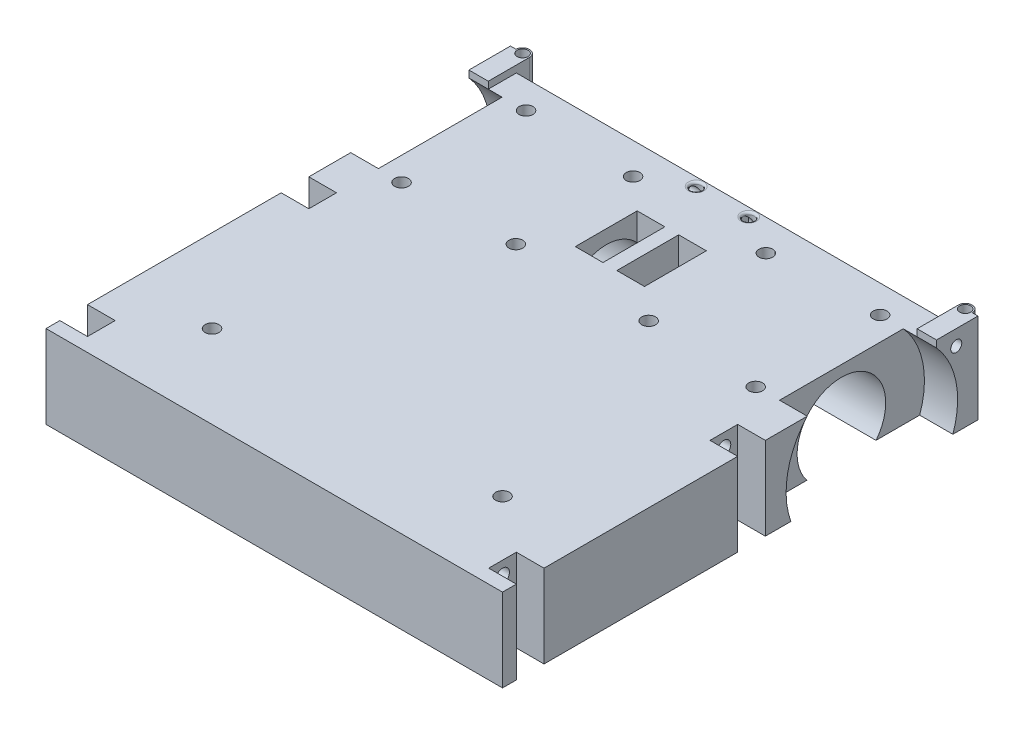
SolidWorks part; units mm, degrees
ref_plane "Plan de face" through (0, 0, 0) normal (0, 0, 1) x (1, 0, 0)
ref_plane "Plan de dessus" through (0, 0, 0) normal (0, 1, 0) x (1, 0, 0)
ref_plane "Plan de droite" through (0, 0, 0) normal (1, 0, 0) x (0, 0, -1)
sketch "Esquisse2" plane through (0, 0, 0) normal (0, 1, 0) x (1, 0, 0)
  line L1 (82.5, 82.5) -> (-82.5, 82.5)
  line L2 (82.5, 82.5) -> (82.5, -82.5)
  line L3 (82.5, -82.5) -> (-82.5, -82.5)
  line L4 (-82.5, 82.5) -> (-82.5, -82.5)
  line L5 (82.5, 82.5) -> (-82.5, -82.5) construction
  line L6 (82.5, -82.5) -> (-82.5, 82.5) construction
  point P0 (0, 0)
  dimension "D1" = 165
  dimension "D2" = 165
extrude "BASE" add sketch "Esquisse2" along normal blind 30
sketch "Esquisse3" plane through (82.5, 0, 0) normal (1, 0, 0) x (0, 0, -1)
  line L0 (82.5, 10) -> (31.0775, 10) construction
  line L1 (82.5, 30) -> (82.5, 0) construction
  line L2 (-82.5, 0) -> (82.5, 0) construction
  circle A0 centre (50, 10) radius 15
  point P4 (50, 10)
  dimension "D3" = 30
  dimension "D1" = 32.5
  dimension "D2" = 10
extrude "BLOC MOTEUR 1." cut sketch "Esquisse3" against normal blind 80
sketch "Esquisse4" plane through (0, 0, 0) normal (0, -1, 0) x (1, 0, 0)
  line L0 (2.5, -61.1803) -> (82.5, -61.1803) construction
  line L1 (2.5, -38.8197) -> (12.5, -38.8197)
  line L2 (2.5, -38.8197) -> (2.5, -61.1803)
  line L3 (2.5, -61.1803) -> (12.5, -61.1803)
  line L4 (12.5, -38.8197) -> (12.5, -61.1803)
  dimension "D1" = 10
extrude "ACCES MOTEUR" cut sketch "Esquisse4" against normal blind 37
ref_plane "PLAN SYM " through (0, 0, 0) normal (1, 0, 0) x (0, 0, -1)
sketch "Esquisse6" plane through (82.5, 0, 0) normal (1, 0, 0) x (0, 0, -1)
  line L0 (35, 10) -> (65, 10) construction
  arc A0 (38.8197, 20) -> (38.8197, 0) centre (50, 10) ccw construction
  arc A1 (61.1803, 0) -> (38.8197, 0) centre (50, 10) ccw construction
  circle A2 centre (50, 10) radius 16.01
  dimension "D1" = 32.02
extrude "BLOC MOTEUR 2" cut sketch "Esquisse6" against normal blind 37
mirror "SYM BLOC MOTEUR" about plane through (0, 0, 0) normal (1, 0, 0) of "ACCES MOTEUR", "BLOC MOTEUR 1.", "BLOC MOTEUR 2"
sketch "Esquisse7" plane through (0, 0, 0) normal (0, -1, 0) x (1, 0, 0)
  line L0 (-64, -37.4972) -> (-64, -72.5028) construction
  line L1 (-82.5, -37.4972) -> (-45.5, -37.4972) construction
  line L2 (-24, -38.8197) -> (-24, -67.469) construction
  line L3 (-45.5, -38.8197) -> (-2.5, -38.8197) construction
  line L4 (-45.5, -62.5028) -> (-82.5, -62.5028) construction
  line L5 (-2.5, -61.1803) -> (-45.5, -61.1803) construction
  line L6 (-64, -37.4972) -> (-64, -13.9891) construction
  line L7 (-24, -71.1803) -> (-24, -20.9291) construction
  circle A0 centre (-64, -27.4972) radius 2.5
  circle A1 centre (-24, -28.8197) radius 2.5
  circle A2 centre (-24, -71.1803) radius 2.5
  circle A3 centre (-64, -72.5028) radius 2.5
  point P8 (-64, -27.4972)
  point P9 (-64, -72.5028)
  point P10 (-24, -71.1803)
  point P11 (-24, -28.8197)
  dimension "D5" = 5
  dimension "D6" = 5
  dimension "D7" = 5
  dimension "D8" = 5
  dimension "D1" = 10
  dimension "D2" = 10
  dimension "D3" = 10
  dimension "D4" = 10
extrude "VIS MOTEUR" cut sketch "Esquisse7" against normal through all
mirror "SYM VIS" about plane through (0, 0, 0) normal (1, 0, 0) of "VIS MOTEUR"
sketch "Esquisse8" plane through (0, 0, 0) normal (0, -1, 0) x (1, 0, 0)
  line L0 (-82.5, 82.5) -> (82.5, 82.5) construction
  line L1 (-82.5, -37.4972) -> (-82.5, 82.5) construction
  line L2 (82.5, 82.5) -> (82.5, -37.4972) construction
  circle A0 centre (-52.5, 52.5) radius 2.5
  circle A1 centre (52.5, 52.5) radius 2.5
  point P0 (-52.5, 52.5)
  point P1 (52.5, 52.5)
  dimension "D5" = 5
  dimension "D6" = 5
  dimension "D1" = 30
  dimension "D2" = 30
  dimension "D3" = 30
  dimension "D4" = 30
extrude "VIS PATIN" cut sketch "Esquisse8" against normal through all
sketch "Esquisse12" plane through (-82.5, 0, 0) normal (-1, 0, 0) x (0, 0, 1)
  circle A0 centre (-50, 10) radius 30
  dimension "D1" = 60
extrude "ESPACE ROUE " cut sketch "Esquisse12" against normal blind 10
mirror "SYM ESPACE ROUE" about plane through (0, 0, 0) normal (1, 0, 0) of "ESPACE ROUE "
sketch "Esquisse14" plane through (0, 30, 0) normal (0, 1, 0) x (1, 0, 0)
  line L0 (-82.5, 82.5) -> (82.5, 82.5) construction
  line L1 (-80, 79.7079) -> (-80, 91.2393) construction
  line L2 (-82.5, 87.2451) -> (-82.5, 82.5)
  line L3 (-77.5, 87.2451) -> (-77.5, 82.5)
  line L4 (1.7488, 70.1549) -> (0, 73.4609) construction
  line L5 (0, 73.4609) -> (0, 103.9135) construction
  line L6 (77.5, 87.2451) -> (77.5, 82.5)
  line L7 (82.5, 87.2451) -> (82.5, 82.5)
  arc A0 (-77.5, 87.2451) -> (-82.5, 87.2451) centre (-80, 87.2451) ccw
  circle A1 centre (-80, 87.2451) radius 2
  circle A2 centre (80, 87.2451) radius 2
  arc A3 (77.5, 87.2451) -> (82.5, 87.2451) centre (80, 87.2451) cw
  point P4 (-80, 82.5)
  point P5 (0, 82.5)
  line M29 (82.5, 82.5) -> (-82.5, 82.5)
  dimension "D3" = 4
  dimension "D1" = 165
  dimension "D2" = 80
extrude "FIXE PORTE 1" add sketch "Esquisse14" against normal blind 10 and the other way blind 2.5 contours L3 A0 L2 A1 M29 | A3 L6 L7 A2 M29
sketch "Esquisse15" plane through (0, 30, 0) normal (0, 1, 0) x (1, 0, 0)
  line L0 (82.5, 72.3607) -> (72.5, 72.3607) construction
  line L1 (-77.5, 82.5) -> (-82.5, 82.5)
  line L2 (-77.5, 82.5) -> (-77.5, 72.3607)
  line L3 (-77.5, 72.3607) -> (-82.5, 72.3607)
  line L4 (-82.5, 82.5) -> (-82.5, 72.3607)
  line L5 (82.5, 82.5) -> (77.5, 82.5)
  line L6 (82.5, 82.5) -> (82.5, 72.3607)
  line L7 (82.5, 72.3607) -> (77.5, 72.3607)
  line L8 (77.5, 82.5) -> (77.5, 72.3607)
extrude "FIXE PORTE 2" add sketch "Esquisse15" along normal blind 2.5
sketch "Esquisse16" plane through (0, 0, 0) normal (0, -1, 0) x (1, 0, 0)
  line L0 (-82.5, -87.2451) -> (-82.5, -82.5)
  line L1 (-82.5, -82.5) -> (-77.5, -82.5)
  line L2 (82.5, -82.5) -> (-82.5, -82.5) construction
  line L3 (-77.5, -82.5) -> (-82.5, -82.5) construction
  line L4 (-77.5, -82.5) -> (-77.5, -87.2451)
  line L5 (0, -73.149) -> (0, -105.1692) construction
  line L6 (82.5, -87.2451) -> (82.5, -82.5)
  line L7 (77.5, -82.5) -> (77.5, -87.2451)
  circle A0 centre (-80, -87.2451) radius 2
  arc A1 (-82.5, -87.2451) -> (-77.5, -87.2451) centre (-80, -87.2451) ccw
  arc A2 (82.5, -87.2451) -> (77.5, -87.2451) centre (80, -87.2451) cw
  circle A3 centre (80, -87.2451) radius 2
  line M40 (-82.5, -82.5) -> (82.5, -82.5)
extrude "FIXE PORTE 3" add sketch "Esquisse16" against normal blind 10 contours L0 A1 L4 A0 M40 | A2 L6 L7 A3 M40
sketch "Esquisse18" plane through (82.5, 0, 0) normal (1, 0, 0) x (0, 0, -1)
  line L0 (82.5, 30) -> (72.3607, 30) construction
  line L1 (82.5, 20) -> (82.5, 30) construction
  circle A0 centre (79.5, 27) radius 2
  dimension "D1" = 4
  dimension "D2" = 3
  dimension "D3" = 3
extrude "VIDE CORDE COTE" cut sketch "Esquisse18" against normal blind 75
sketch "Esquisse19" plane through (0, 30, 0) normal (0, 1, 0) x (1, 0, 0)
  line L0 (0, 82.5) -> (0, 66.3305) construction
  line L1 (77.5, 82.5) -> (-77.5, 82.5) construction
  line L2 (82.5, 79.5) -> (9.5, 79.5) construction
  line L3 (82.5, 87.2451) -> (82.5, 72.3607) construction
  circle A0 centre (9.5, 79.5) radius 2
  dimension "D3" = 4
  dimension "D1" = 3
  dimension "D2" = 73
extrude "VIDEO CORDE HAUT" cut sketch "Esquisse19" against normal blind 5
mirror "SYM CORDE" about plane through (0, 0, 0) normal (1, 0, 0) of "VIDEO CORDE HAUT", "VIDE CORDE COTE"
fillet "CONGE CORDE" radius 0.8 2 edges at (-9.5, 30, -77.5) (9.5, 30, -77.5)
sketch "Esquisse20" plane through (82.5, 0, 0) normal (1, 0, 0) x (0, 0, -1)
  line L0 (72.3607, 30) -> (72.3607, 32.5)
  line L1 (72.3607, 32.5) -> (87.3607, 32.5)
  line L2 (87.3607, 32.5) -> (87.3607, 0)
  line L3 (87.3607, 0) -> (78.2843, 0)
  circle A0 centre (79.5, 27) radius 2
  arc A1 (78.2843, 0) -> (72.3607, 30) centre (50, 10) ccw
  dimension "D1" = 15
extrude "BOSS MAX PORTE" add sketch "Esquisse20" along normal blind 2
mirror "SYM MAX PORTE" about plane through (0, 0, 0) normal (1, 0, 0) of "BOSS MAX PORTE"
ref_point "POINT CONST PORTE 45" parameters "D1"=2
ref_plane "PLAN PORTE 45" through (82.4008, 0.3109, -87.453) normal (0.6858, 0.0026, -0.7278) x (-0.7278, 0.0024, -0.6858)
sketch "Esquisse23" plane through (82.5, 0, 0) normal (1, 0, 0) x (0, 0, -1)
  line L0 (20.0461, 11.6625) -> (20.0461, -3.5531) construction
  line L1 (-77.5, 30) -> (-67.5, 30)
  line L2 (-77.5, 30) -> (-77.5, 0)
  line L3 (-77.5, 0) -> (-67.5, 0)
  line L4 (-67.5, 30) -> (-67.5, 0)
  line L6 (-82.5, 0) -> (21.7157, 0) construction
  line L8 (-82.5, 30) -> (-82.5, 0) construction
  line L9 (-82.5, 30) -> (27.6393, 30) construction
  line L10 (12.5, 0) -> (2.5, 0)
  line L11 (12.5, 0) -> (12.5, 30)
  line L12 (12.5, 30) -> (2.5, 30)
  line L13 (2.5, 0) -> (2.5, 30)
  arc A1 (27.6393, 30) -> (21.7157, 0) centre (50, 10) ccw construction
  point P19 (7.5, 0)
  dimension "D1" = 5
  dimension "D2" = 10
  dimension "D4" = 10
  dimension "D5" = 90
extrude "VIDE TIGE" cut sketch "Esquisse23" against normal blind 10
mirror "SYM TIGE" about plane through (0, 0, 0) normal (1, 0, 0) of "VIDE TIGE"
sketch "Esquisse25" plane through (72.5, 0, 0) normal (1, 0, 0) x (0, 0, -1)
  line L0 (-77.5, 30) -> (-67.5, 0) construction
  line L1 (-67.5, 0) -> (-72.5, 0) construction
  line L2 (-77.5, 0) -> (-67.5, 0) construction
  line L3 (-72.5, 0) -> (-72.5, 30) construction
  line L4 (-67.5, 30) -> (-77.5, 30) construction
  line L5 (2.5, 30) -> (-67.5, 0) construction
  line L6 (-67.5, 0) -> (-67.5, 30) construction
  line L7 (-67.5, 30) -> (-32.5, 30) construction
  line L8 (-67.5, 30) -> (2.5, 30) construction
  line L9 (-32.5, 30) -> (-32.5, -2.9576) construction
  circle A0 centre (-72.5, 25) radius 2.5
  circle A1 centre (-72.5, 15) radius 2.5
  circle A2 centre (-72.5, 5) radius 2.5
  circle A3 centre (7.5, 5) radius 2.5
  circle A4 centre (7.5, 25) radius 2.5
  circle A5 centre (7.5, 15) radius 2.5
  dimension "D1" = 5
  dimension "D2" = 5
  dimension "D3" = 5
  dimension "D4" = 10
  dimension "D5" = 10
  dimension "D6" = 5
extrude "VIDE VIS" cut sketch "Esquisse25" against normal up to next
